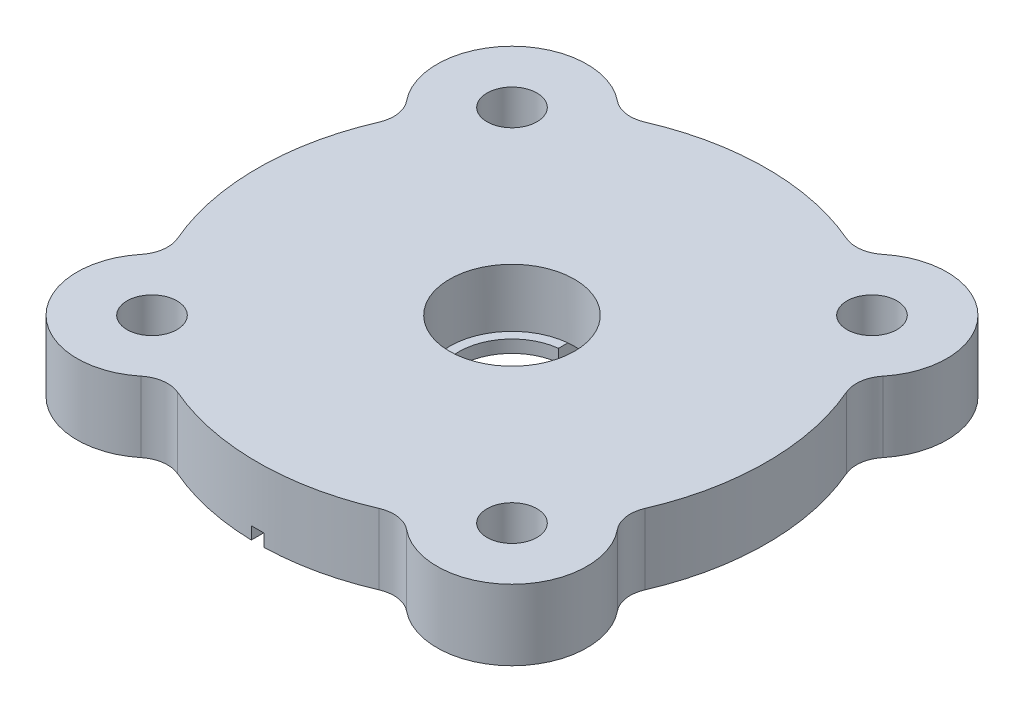
SolidWorks part; units mm, degrees
material "1060 Alloy"
ref_plane "Front" through (0, 0, 0) normal (0, 0, 1) x (1, 0, 0)
ref_plane "Top" through (0, 0, 0) normal (0, 1, 0) x (1, 0, 0)
ref_plane "Right" through (0, 0, 0) normal (1, 0, 0) x (0, 0, -1)
sketch "Sketch1" plane through (0, 0, 0) normal (0, 1, 0) x (1, 0, 0)
  line L0 (0, 0) -> (0, 40.75) construction
  circle A0 centre (-28.8146, 28.8146) radius 4
  circle A1 centre (28.8146, 28.8146) radius 4
  circle A2 centre (28.8146, -28.8146) radius 4
  circle A3 centre (-28.8146, -28.8146) radius 4
  circle A4 centre (0, 0) radius 8.5
  arc A5 (-21.2538, 38.1331) -> (-38.1331, 21.2538) centre (-28.8146, 28.8146) ccw
  arc A6 (38.1331, 21.2538) -> (21.2538, 38.1331) centre (28.8146, 28.8146) ccw
  arc A7 (21.2538, -38.1331) -> (38.1331, -21.2538) centre (28.8146, -28.8146) ccw
  arc A8 (-38.1331, -21.2538) -> (-21.2538, -38.1331) centre (-28.8146, -28.8146) ccw
  arc A9 (-37.4239, 16.1249) -> (-37.4239, -16.1249) centre (0, 0) ccw
  arc A10 (-16.1249, -37.4239) -> (16.1249, -37.4239) centre (0, 0) ccw
  arc A11 (37.4239, -16.1249) -> (37.4239, 16.1249) centre (0, 0) ccw
  arc A12 (-16.1249, 37.4239) -> (-21.2538, 38.1331) centre (-18.1035, 42.0158) cw
  arc A13 (16.1249, 37.4239) -> (-16.1249, 37.4239) centre (0, 0) ccw
  arc A14 (21.2538, 38.1331) -> (16.1249, 37.4239) centre (18.1035, 42.0158) cw
  arc A15 (38.1331, 21.2538) -> (37.4239, 16.1249) centre (42.0158, 18.1035) ccw
  arc A16 (37.4239, -16.1249) -> (38.1331, -21.2538) centre (42.0158, -18.1035) ccw
  arc A17 (21.2538, -38.1331) -> (16.1249, -37.4239) centre (18.1035, -42.0158) ccw
  arc A18 (-16.1249, -37.4239) -> (-21.2538, -38.1331) centre (-18.1035, -42.0158) ccw
  arc A19 (-37.4239, -16.1249) -> (-38.1331, -21.2538) centre (-42.0158, -18.1035) cw
  arc A20 (-37.4239, 16.1249) -> (-38.1331, 21.2538) centre (-42.0158, 18.1035) ccw
  point P0 (0, 0)
  point P17 (0, 0)
  point P27 (0, 0)
  dimension "D5" = 8
  dimension "D6" = 17
  dimension "D1" = 5
  dimension "D2" = 12
  dimension "D3" = 40.75
  dimension "D4" = 4
  dimension "D8" = 4
extrude "body and main holes" add sketch "Sketch1" along normal blind 11.3
sketch "Sketch3" plane through (0, 11.3, 0) normal (0, -1, 0) x (1, 0, 0)
  circle A0 centre (0, 0) radius 10
  dimension "D1" = 20
extrude "seal bore" cut sketch "Sketch3" along normal blind 9.3
sketch "Sketch4" plane through (0, 0, 0) normal (0, -1, 0) x (1, 0, 0)
  line L0 (0, 0) -> (0, 40.75) construction
  line L2 (-1, 40.75) -> (1, 40.75)
  line L3 (-1, 40.75) -> (-1, -40.75)
  line L4 (-1, -40.75) -> (1, -40.75)
  line L5 (1, 40.75) -> (1, -40.75)
  line L6 (-1, 40.75) -> (1, -40.75) construction
  line L7 (-1, -40.75) -> (1, 40.75) construction
  arc A0 (16.1249, 37.4239) -> (-16.1249, 37.4239) centre (0, 0) ccw construction
  arc A1 (-16.1249, -37.4239) -> (16.1249, -37.4239) centre (0, 0) ccw construction
  point P6 (0, 0)
  dimension "D1" = 2
extrude "Cut-Extrude1" cut sketch "Sketch4" against normal blind 2
equation "\"D3@Sketch1\"=\"square plate bolt pattern diameter\"/2"
equation "\"D1@body and main holes\"=\"small seal plate thickness\""
equation "\"D1@Sketch3\"=\"small seal OD\""
equation "\"D1@seal bore\"=\"small seal bore\""
equation "\"D5@Sketch1\" = \"square plate bolt bore\""
equation "\"D6@Sketch1\"=\"small seal plate lip ID\""
equation "\"bearing inner race thickness\"= 1mm"
equation "\"bearing bore\"= \"bearing depth\" + 1mm"
equation "\"square plate bolt pattern diameter\"= \"motor OD\" + \"square plate bolt head diameter\" + 4mm"
equation "\"bearing plate thickness\"= \"bearing bore\" + \"bearing plate stop depth\" + \"shaft bearing stop length\""
equation "\"bearing plate stop ID\"= \"bearing OD\" - 4mm"
equation "\"bearing plate stop depth\"= 3mm"
equation "\"square plate bolt bore\"= 8mm"
equation "\"square plate bolt head diameter\"= 13.5mm"
equation "\"motor OD\"= 64mm"
equation "\"bearing OD\"= 30mm"
equation "\"bearing depth\"= 9mm"
equation "\"motor mount post radius\"= ( 3 * \"square plate bolt bore\" ) / 2"
equation "\"D2@Sketch1\"=\"motor mount post radius\""
equation "\"bearing ID\"= 10mm"
equation "\"bearing outer race thickness\"= 1mm"
equation "\"small seal OD\"= 20mm"
equation "\"small seal ID\"= 8mm"
equation "\"small seal depth\"= 8.3mm"
equation "\"small seal bore\"= \"small seal depth\" + 1mm"
equation "\"big seal OD\"= 27mm"
equation "\"big seal ID\"= 15mm"
equation "\"big seal depth\"= 8.3mm"
equation "\"big seal bore\"= \"big seal depth\" + 1mm"
equation "\"small seal plate lip depth\"= 2mm"
equation "\"small seal plate lip ID\"= \"small seal OD\" - 3mm"
equation "\"small seal plate thickness\"= \"small seal plate lip depth\" + \"small seal bore\""
